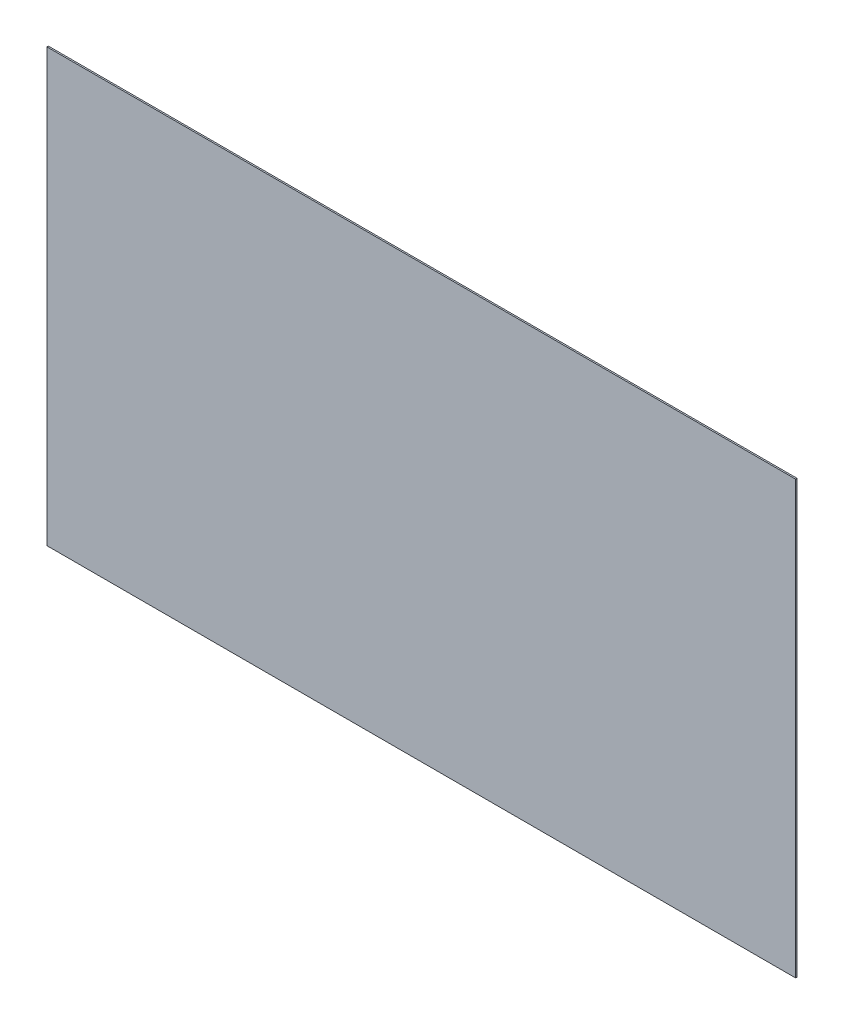
SolidWorks part; units mm, degrees
material "瓦楞纸"
ref_plane "前视基准面" through (0, 0, 0) normal (0, 0, 1) x (1, 0, 0)
ref_plane "上视基准面" through (0, 0, 0) normal (0, 1, 0) x (1, 0, 0)
ref_plane "右视基准面" through (0, 0, 0) normal (1, 0, 0) x (0, 0, -1)
sketch "草图1" plane through (0, 0, 0) normal (0, 0, 1) x (1, 0, 0)
  line L1 (-26, -15) -> (26, -15)
  line L2 (-26, -15) -> (-26, 15)
  line L3 (-26, 15) -> (26, 15)
  line L4 (26, -15) -> (26, 15)
  line L5 (-26, -15) -> (26, 15) construction
  line L6 (-26, 15) -> (26, -15) construction
  point P0 (0, 0)
  dimension "D1" = 52
  dimension "D2" = 30
extrude "凸台-拉伸1" add sketch "草图1" along normal blind 0.1
